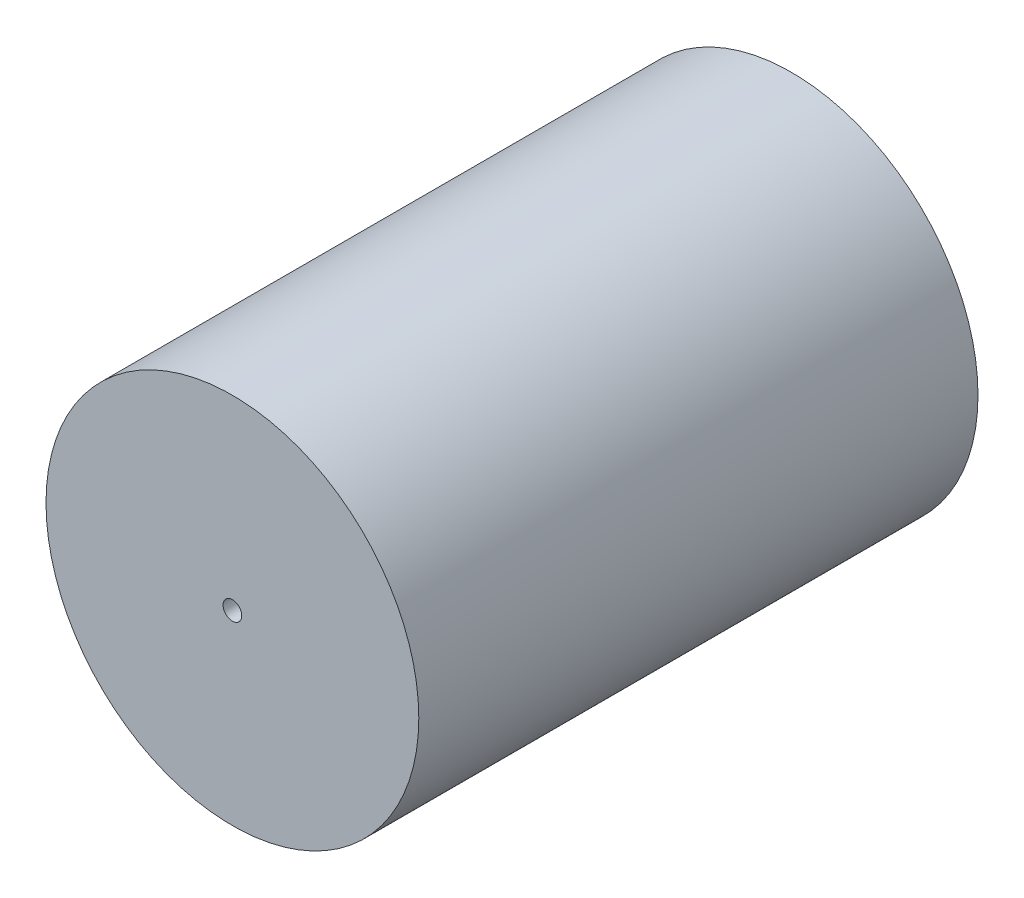
SolidWorks part; units mm, degrees
ref_plane "Front Plane" through (0, 0, 0) normal (0, 0, 1) x (1, 0, 0)
ref_plane "Top Plane" through (0, 0, 0) normal (0, 1, 0) x (1, 0, 0)
ref_plane "Right Plane" through (0, 0, 0) normal (1, 0, 0) x (0, 0, -1)
sketch "Sketch1" plane through (0, 0, 0) normal (0, 0, 1) x (1, 0, 0)
  circle A0 centre (0, 0) radius 5
  circle A1 centre (0, 0) radius 100
  dimension "D1" = 10
  dimension "D2" = 200
extrude "Boss-Extrude1" add sketch "Sketch1" along normal blind 300
